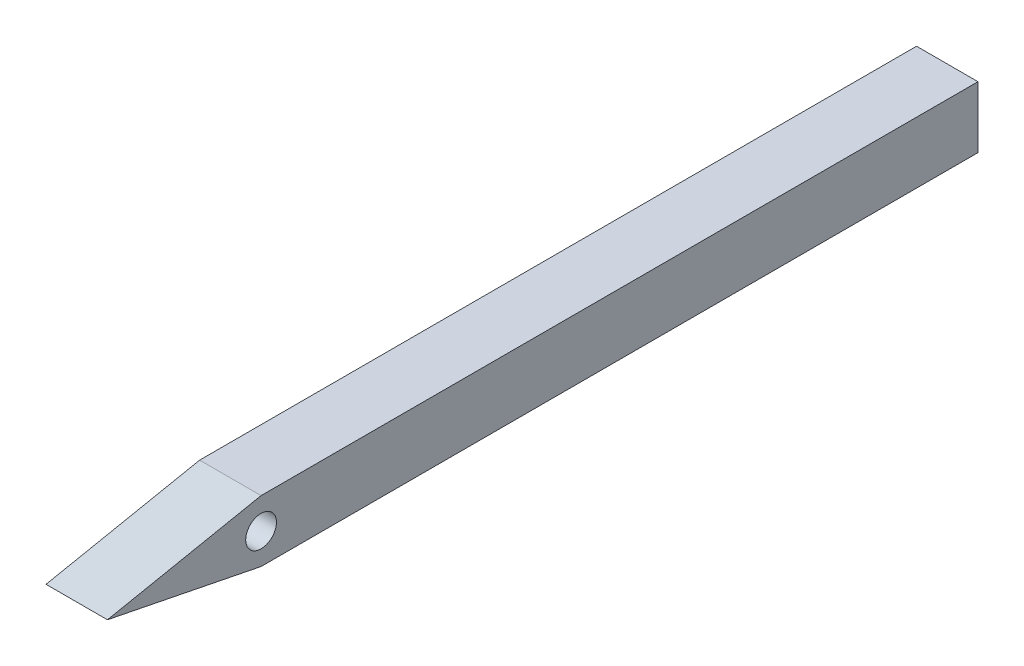
SolidWorks part; units mm, degrees
ref_plane "Front Plane" through (0, 0, 0) normal (0, 0, 1) x (1, 0, 0)
ref_plane "Top Plane" through (0, 0, 0) normal (0, 1, 0) x (1, 0, 0)
ref_plane "Right Plane" through (0, 0, 0) normal (1, 0, 0) x (0, 0, -1)
sketch "Sketch1" plane through (0, 0, 0) normal (1, 0, 0) x (0, 0, -1)
  line L0 (0, 0) -> (-70, 0)
  line L1 (0, 0) -> (0, 6)
  line L2 (0, 6) -> (-70, 6)
  line L4 (-70, 6) -> (-70, 0) construction
  line L5 (-70, 6) -> (-85, 3)
  line L6 (-85, 3) -> (-70, 0)
  dimension "D2" = 6
extrude "Boss-Extrude1" add sketch "Sketch1" along normal blind 6
sketch "Sketch2" plane through (6, 0, 0) normal (1, 0, 0) x (0, 0, -1)
  line L0 (-70, 6) -> (-70, 0) construction
  circle A0 centre (-70, 3) radius 1.5
extrude "Cut-Extrude1" cut sketch "Sketch2" against normal blind 6
